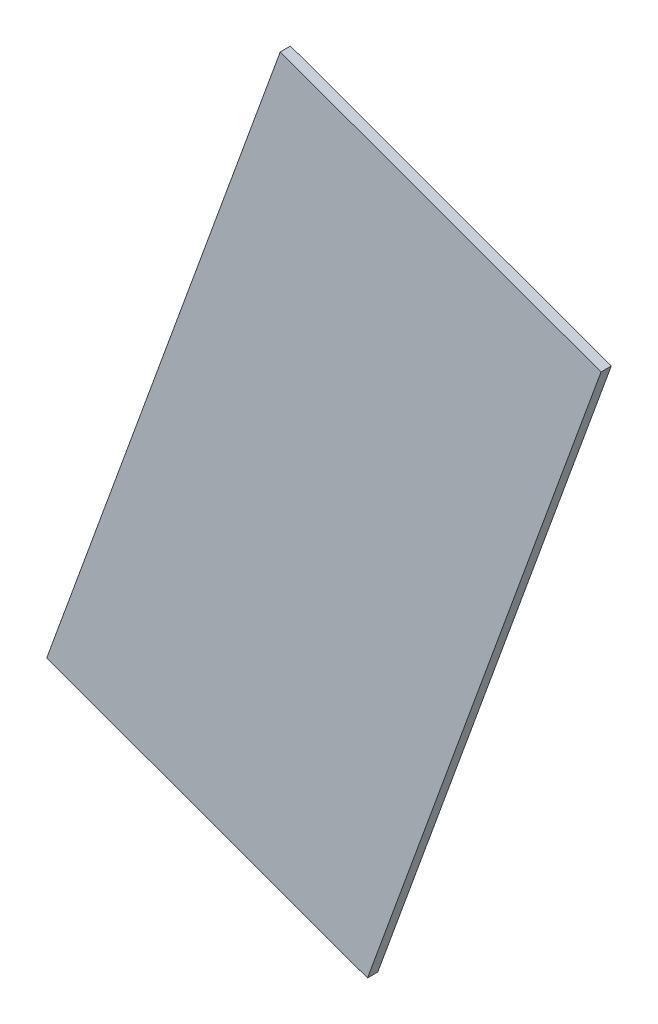
SolidWorks part; units mm, degrees
material "Thornel Mat VMA"
ref_plane "前视基准面" through (0, 0, 0) normal (0, 0, 1) x (1, 0, 0)
ref_plane "上视基准面" through (0, 0, 0) normal (0, 1, 0) x (1, 0, 0)
ref_plane "右视基准面" through (0, 0, 0) normal (1, 0, 0) x (0, 0, -1)
other "Configuration Table"
sketch "草图1" plane through (0, 0, 0) normal (0, 0, 1) x (1, 0, 0)
  line L0 (413.793, 649.9646) -> (482.197, 837.9031)
  line L3 (413.793, 649.9646) -> (319.8237, 684.1666)
  line L4 (319.8237, 684.1666) -> (388.2277, 872.1051)
  line L7 (482.197, 837.9031) -> (388.2277, 872.1051)
  line L9 (328.5815, 686.2999) -> (326.8714, 681.6014) construction
  dimension "D1" = 200
  dimension "D2" = 100
  dimension "D3" = 7.5
extrude "凸台-拉伸1" add sketch "草图1" along normal blind 3
